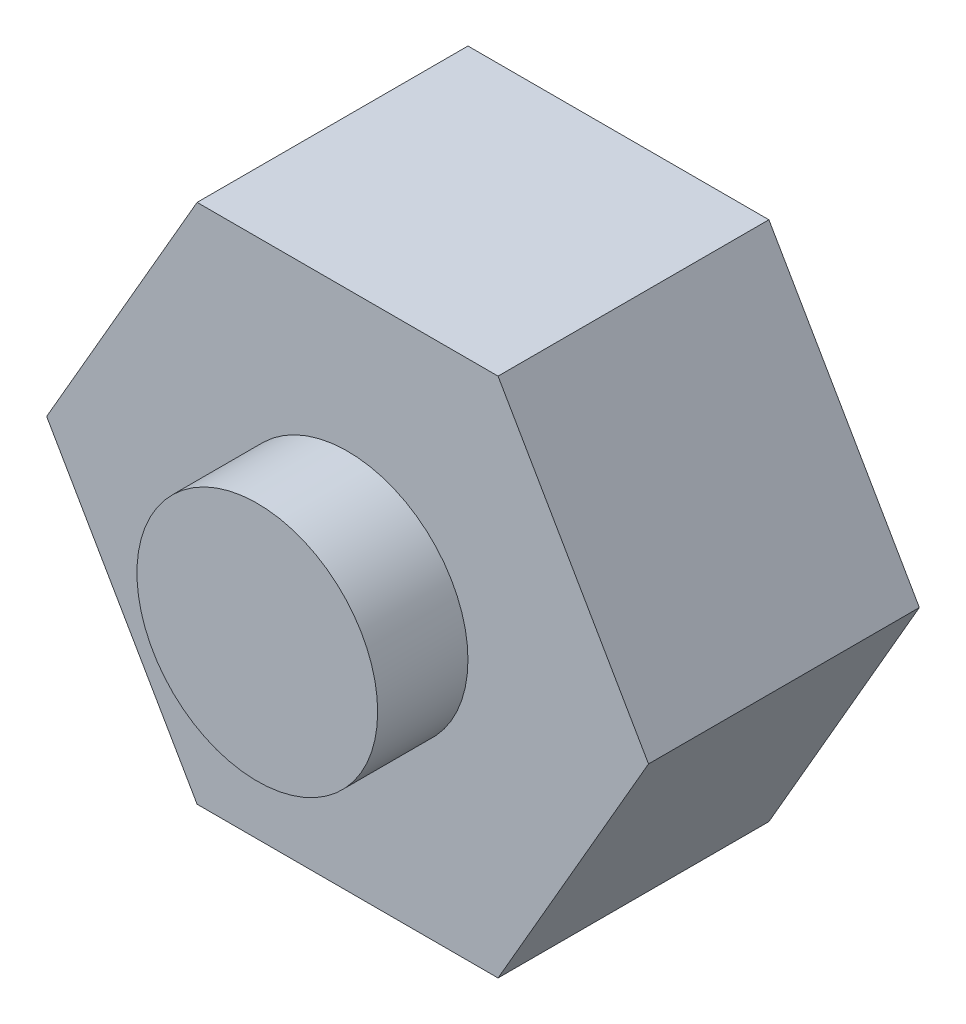
SolidWorks part; units mm, degrees
ref_plane "前视基准面" through (0, 0, 0) normal (0, 0, 1) x (1, 0, 0)
ref_plane "上视基准面" through (0, 0, 0) normal (0, 1, 0) x (1, 0, 0)
ref_plane "右视基准面" through (0, 0, 0) normal (1, 0, 0) x (0, 0, -1)
other "Configuration Table"
sketch "草图1" plane through (0, 0, 0) normal (0, 0, 1) x (1, 0, 0)
  circle A0 centre (0, 0) radius 8
extrude "凸台-拉伸1" add sketch "草图1" along normal blind 24
sketch "草图2" plane through (0, 0, 0) normal (0, 0, 1) x (1, 0, 0)
  circle A0 centre (0, 0) radius 42
extrude "凸台-拉伸2" add sketch "草图2" along normal blind 18
sketch "草图3" plane through (0, 0, 18) normal (0, 0, 1) x (1, 0, 0)
  line L0 (20, 0) -> (10, 17.3205)
  line L1 (10, 17.3205) -> (-10, 17.3205)
  line L2 (-10, 17.3205) -> (-20, 0)
  line L3 (-20, 0) -> (-10, -17.3205)
  line L4 (-10, -17.3205) -> (10, -17.3205)
  line L5 (10, -17.3205) -> (20, 0)
extrude "切除-拉伸1" cut sketch "草图3" against normal through all flip side to cut
